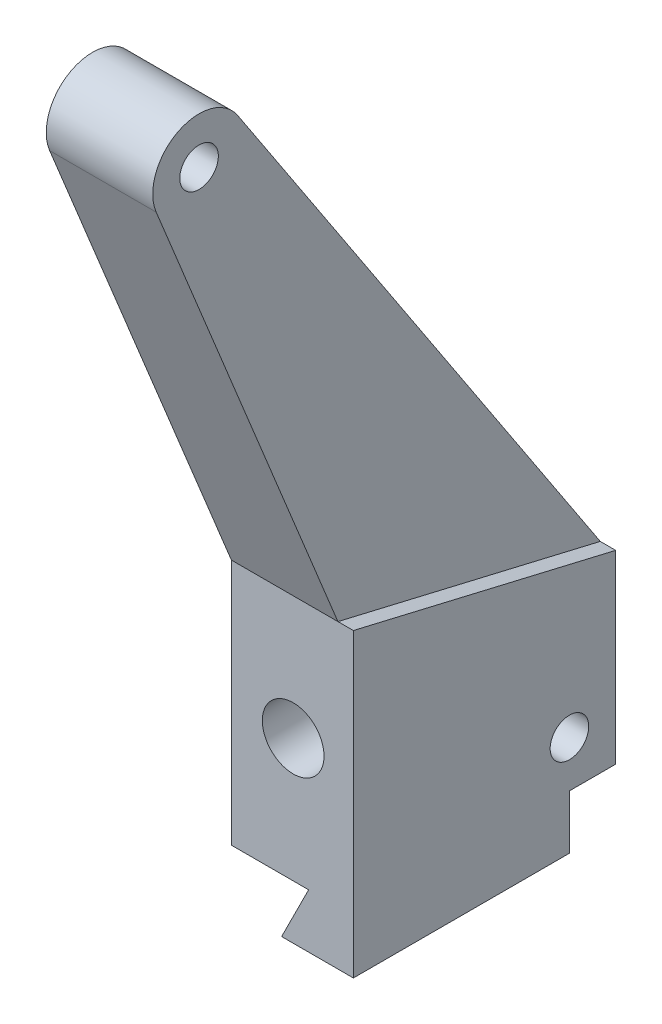
SolidWorks part; units mm, degrees
ref_plane "Front Plane" through (0, 0, 0) normal (0, 0, 1) x (1, 0, 0)
ref_plane "Top Plane" through (0, 0, 0) normal (0, 1, 0) x (1, 0, 0)
ref_plane "Right Plane" through (0, 0, 0) normal (1, 0, 0) x (0, 0, -1)
sketch "Sketch1" plane through (0, 0, 0) normal (1, 0, 0) x (0, 0, -1)
  line L0 (0, 0) -> (0, 16)
  line L1 (0, 16) -> (-23.4951, 51.6508)
  line L2 (-17, 20) -> (-17, 0)
  line L3 (-17, 0) -> (0, 0)
  line L4 (-17, 20) -> (-28.7777, 48.8667)
  arc A0 (-23.4951, 51.6508) -> (-28.7777, 48.8667) centre (-26, 50) ccw
  circle A1 centre (-26, 50) radius 1.25
  dimension "D4" = 6
  dimension "D5" = 9
  dimension "D6" = 50
  dimension "D7" = 2.5
  dimension "D1" = 20
  dimension "D2" = 16
  dimension "D3" = 17
extrude "Boss-Extrude1" add sketch "Sketch1" along normal blind 8
sketch "Sketch2" plane through (8, 0, 0) normal (1, 0, 0) x (0, 0, -1)
  line L0 (-17, 20) -> (-17, 0) construction
  line L1 (-17, 5) -> (0, 5)
  line L2 (-17, 5) -> (-17, 0)
  line L3 (-17, 0) -> (0, 0)
  line L4 (0, 5) -> (0, 0)
  line L5 (0, 0) -> (0, 16) construction
  dimension "D1" = 5
extrude "Cut-Extrude1" [suppressed] cut sketch "Sketch2" against normal blind 4
sketch "Sketch3" plane through (0, 0, 0) normal (0, 0, -1) x (-1, 0, 0)
  line L0 (-8, 0) -> (-5, 0)
  line L1 (-8, 0) -> (0, 0) construction
  line L2 (-5, 0) -> (-3, 4)
  line L3 (-3, 4) -> (-8, 4)
  line L4 (-8, 0) -> (-8, 16) construction
  line L5 (-8, 4) -> (-8, 0)
  dimension "D1" = 5
  dimension "D2" = 3
  dimension "D3" = 4
extrude "Cut-Extrude2" cut sketch "Sketch3" against normal through all
sketch "Sketch5" plane through (8, 0, 0) normal (1, 0, 0) x (0, 0, -1)
  line L0 (0, 4) -> (0, 16) construction
  line L1 (-17, 4) -> (0, 4) construction
  circle A0 centre (-3, 7) radius 1
  dimension "D1" = 2
  dimension "D3" = 3
  dimension "D2" = 3
hole_wizard "M3x0.5 Tapped Hole1" positions "3DSketch1" profile "Sketch6" tap size "M3x0.5" standard "ANSI Metric" end condition through all
sketch3d "3DSketch1"
  point P0 (8, 7, 3)
sketch "Sketch6" plane through (8, 7, 3) normal (0, 1, 0) x (0, 0, -1)
  line L0 (0, 0) -> (0, 16)
  line L1 (0, 16) -> (1.25, 16)
  line L2 (1.25, 16) -> (1.25, 0)
  line L5 (1.25, 0) -> (0, 0)
  line L11 (0, -6.35) -> (0, 107.95) construction
  dimension "Thread Major Dia." = 2.5
  dimension "Thru Tap Drill Depth" = 16
sketch "Sketch7" plane through (0, 0, 0) normal (0, 0, -1) x (-1, 0, 0)
  line L1 (0, 0) -> (-8, 0)
  line L2 (0, 0) -> (0, 0.5)
  line L3 (0, 0.5) -> (-8, 0.5)
  line L4 (-8, 0) -> (-8, 0.5)
  dimension "D1" = 0.5
  dimension "D2" = 8
extrude "Cut-Extrude3" cut sketch "Sketch7" against normal through all
sketch "Sketch8" plane through (0, 0, 17) normal (0, 0, 1) x (1, 0, 0)
  line L0 (3, 4) -> (8, 4) construction
  line L1 (8, 20) -> (8, 4) construction
  circle A0 centre (4, 12) radius 2
  point P4 (5.5, 4)
  dimension "D1" = 4
  dimension "D2" = 8
  dimension "D3" = 4
extrude "Cut-Extrude4" cut sketch "Sketch8" against normal through all
mirror "Mirror1" about plane through (0, 50, 26) normal (1, 0, 0) of "M3x0.5 Tapped Hole1", "Cut-Extrude4", "Cut-Extrude3", "Cut-Extrude2", "Boss-Extrude1"
sketch "Sketch9" plane through (8, 0, 0) normal (1, 0, 0) x (0, 0, -1)
  line L1 (0, 0.5) -> (-38.6719, 0.5)
  line L2 (0, 0.5) -> (0, 56.9511)
  line L3 (0, 56.9511) -> (-38.6719, 56.9511)
  line L4 (-38.6719, 0.5) -> (-38.6719, 56.9511)
  point P5 (0, 0)
extrude "Cut-Extrude5" cut sketch "Sketch9" against normal blind 8.1
sketch "Sketch10" plane through (0, 0, 0) normal (0, 0, -1) x (-1, 0, 0)
  line L0 (4.75, 0.5) -> (3, 4)
  line L1 (3, 4) -> (0.1, 4)
  line L2 (0.1, 0.5) -> (0.1, 16) construction
  line L3 (0.1, 4) -> (0.1, 0.5)
  line L4 (0.1, 0.5) -> (4.75, 0.5)
extrude "Cut-Extrude6" cut sketch "Sketch10" against normal blind 3
sketch "Sketch12" plane through (-0.1, 0, 0) normal (1, 0, 0) x (0, 0, -1)
  line L0 (-17, 20) -> (-28.7777, 48.8667)
  line L1 (0, 16) -> (-23.4951, 51.6508) construction
  line L2 (-23.4951, 51.6508) -> (0, 16)
  line L3 (0, 16) -> (-17, 20)
  arc A0 (-28.7777, 48.8667) -> (-23.4951, 51.6508) centre (-26, 50) cw
  dimension "D1" = 3
extrude "Cut-Extrude8" cut sketch "Sketch12" against normal blind 1
